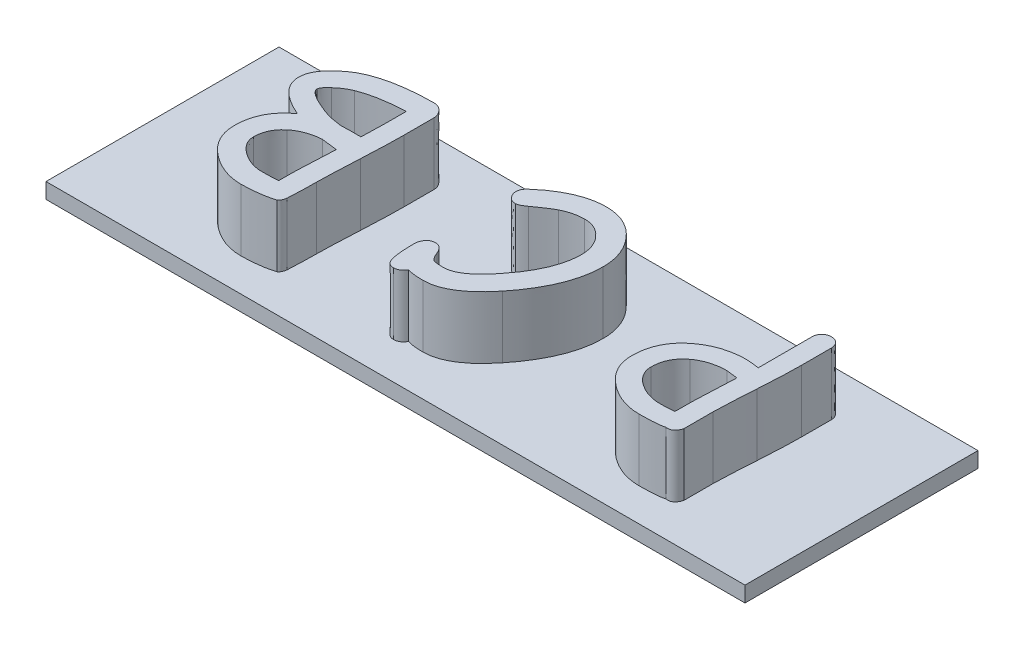
SolidWorks part; units mm, degrees
ref_plane "Front Plane" through (0, 0, 0) normal (0, 0, 1) x (1, 0, 0)
ref_plane "Top Plane" through (0, 0, 0) normal (0, 1, 0) x (1, 0, 0)
ref_plane "Right Plane" through (0, 0, 0) normal (1, 0, 0) x (0, 0, -1)
sketch "Sketch1" plane through (0, 0, 0) normal (0, 1, 0) x (1, 0, 0)
  line L1 (0, 0) -> (114.3, 0)
  line L2 (0, 0) -> (0, 38.1)
  line L3 (0, 38.1) -> (114.3, 38.1)
  line L4 (114.3, 0) -> (114.3, 38.1)
  dimension "D1" = 38.1
  dimension "D2" = 114.3
extrude "Boss-Extrude1" add sketch "Sketch1" along normal blind 2.54
sketch "Sketch2" plane through (0, 2.54, 0) normal (0, 1, 0) x (1, 0, 0)
  line L0 (114.3, 31.75) -> (0, 31.75) construction
  line L1 (114.3, 0) -> (114.3, 38.1) construction
  line L2 (0, 38.1) -> (0, 0) construction
  line L3 (114.3, 38.1) -> (0, 38.1) construction
  text T0 "PCB" font "Comic Sans MS" height 25.4
  dimension "D1" = 6.35
extrude "Boss-Extrude2" add sketch "Sketch2" along normal blind 10.16
